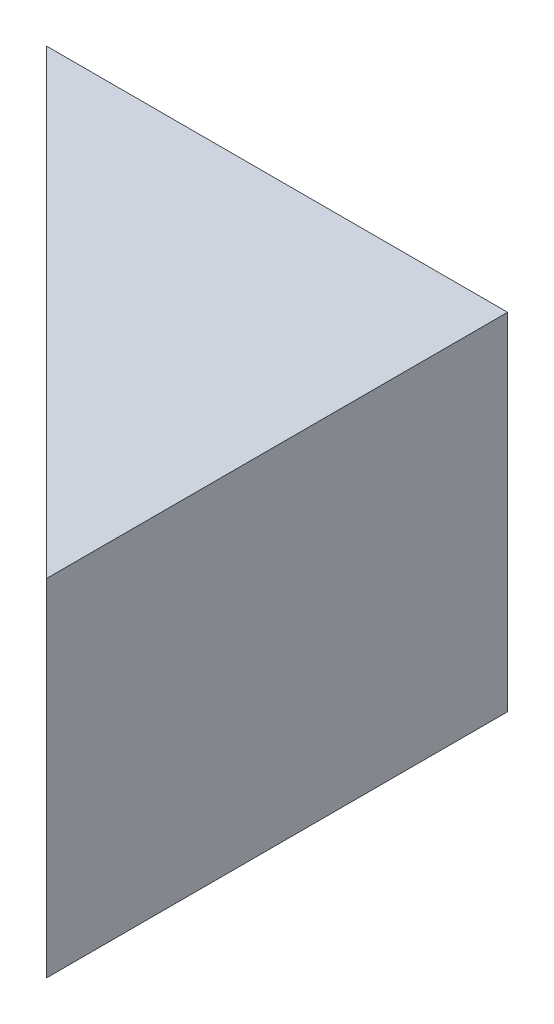
SolidWorks part; units mm, degrees
ref_plane "Ebene vorne" through (0, 0, 0) normal (1, 0, 0) x (0, 1, 0)
ref_plane "Ebene oben" through (0, 0, 0) normal (0, 0, 1) x (0, 1, 0)
ref_plane "Ebene rechts" through (0, 0, 0) normal (0, 1, 0) x (-1, 0, 0)
sketch "Skizze1" plane through (0, 0, 0) normal (0, 1, 0) x (-1, 0, 0)
  line L0 (0, 0) -> (20, 0)
  line L1 (20, 0) -> (0, 20)
  line L2 (0, 20) -> (0, 0)
  dimension "D1" = 20
extrude "Aufsatz-Linear austragen1" add sketch "Skizze1" along normal mid plane 15
